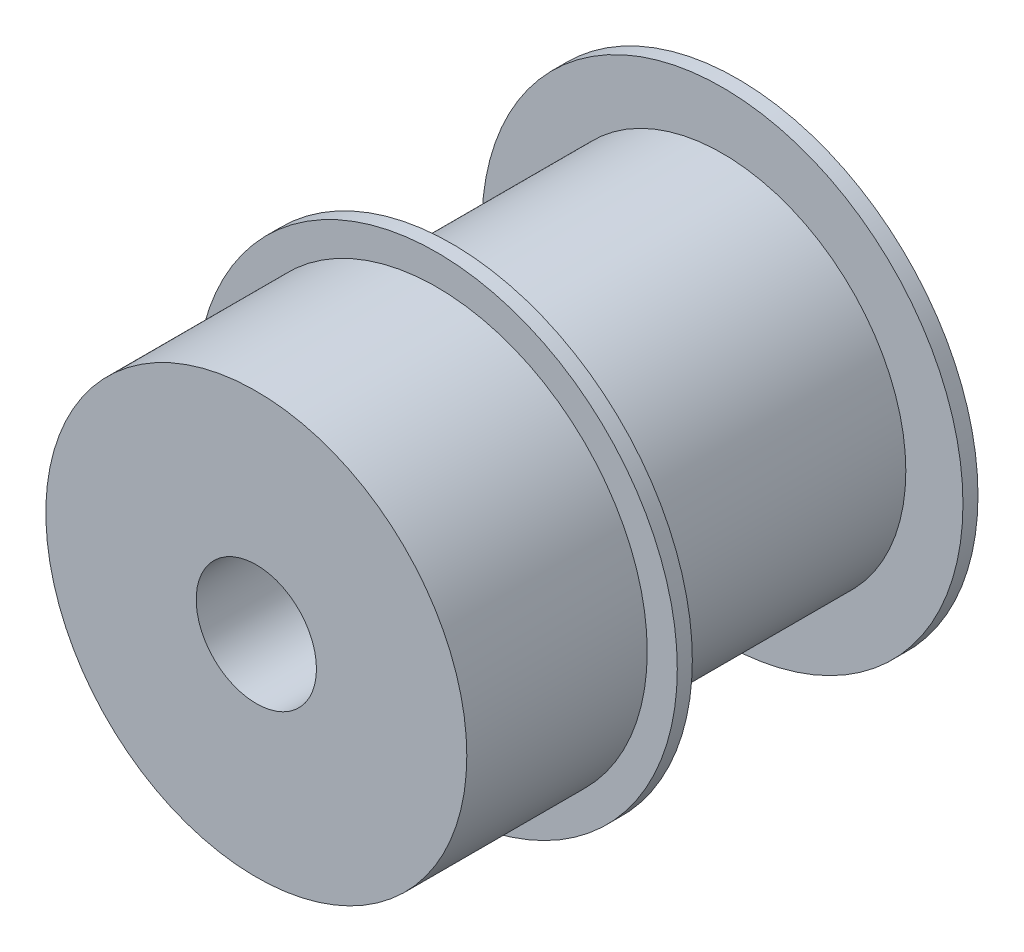
SolidWorks part; units mm, degrees
ref_plane "Plan de face" through (0, 0, 0) normal (0, 0, 1) x (1, 0, 0)
ref_plane "Plan de dessus" through (0, 0, 0) normal (0, 1, 0) x (1, 0, 0)
ref_plane "Plan de droite" through (0, 0, 0) normal (1, 0, 0) x (0, 0, -1)
sketch "Esquisse1" plane through (0, 0, 0) normal (0, 0, 1) x (1, 0, 0)
  circle A0 centre (0, 0) radius 8
extrude "Extrusion1" add sketch "Esquisse1" along normal blind 0.5
sketch "Esquisse2" plane through (0, 0, 0.5) normal (0, 0, 1) x (1, 0, 0)
  circle A0 centre (0, 0) radius 6.1
extrude "Extrusion2" add sketch "Esquisse2" along normal blind 9
sketch "Esquisse3" plane through (0, 0, 9.5) normal (0, 0, 1) x (1, 0, 0)
  circle A0 centre (0, 0) radius 8
extrude "Extrusion3" add sketch "Esquisse3" along normal blind 0.5
sketch "Esquisse4" plane through (0, 0, 10) normal (0, 0, 1) x (1, 0, 0)
  circle A0 centre (0, 0) radius 7
extrude "Extrusion4" add sketch "Esquisse4" along normal blind 6
sketch "Esquisse5" plane through (0, 0, 16) normal (0, 0, 1) x (1, 0, 0)
  circle A0 centre (0, 0) radius 2
extrude "Extrusion5" cut sketch "Esquisse5" against normal through all
